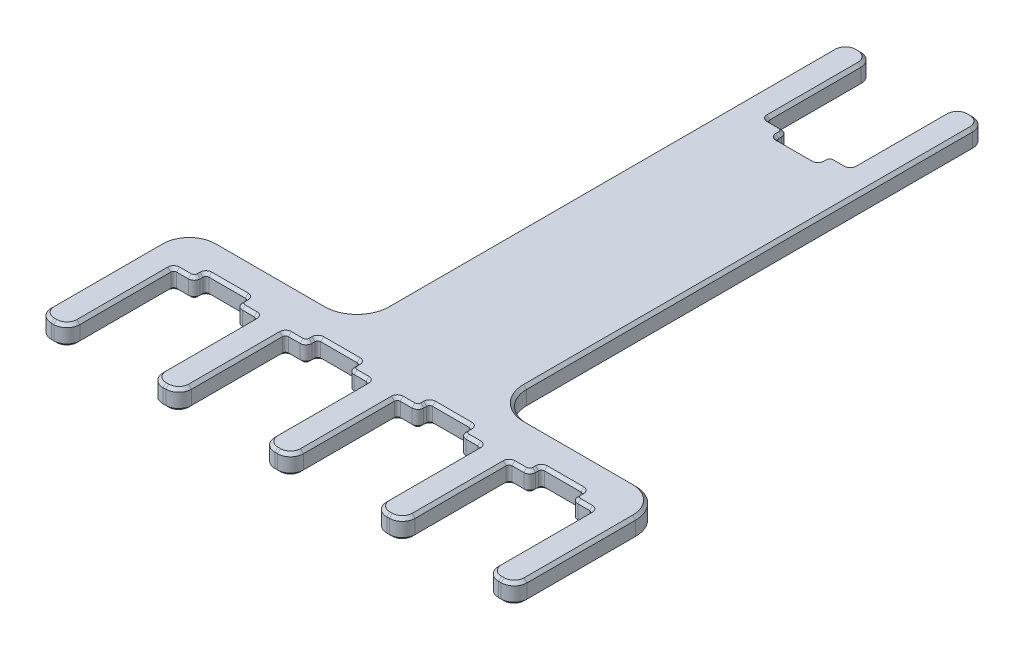
SolidWorks part; units mm, degrees
ref_plane "Front Plane" through (0, 0, 0) normal (0, 0, 1) x (1, 0, 0)
ref_plane "Top Plane" through (0, 0, 0) normal (0, 1, 0) x (1, 0, 0)
ref_plane "Right Plane" through (0, 0, 0) normal (1, 0, 0) x (0, 0, -1)
sketch "Sketch2" plane through (0, 0, 0) normal (0, 1, 0) x (1, 0, 0)
  line L0 (-5.2417, -1.575) -> (8.9583, -1.575)
  line L1 (-24.2917, -1.575) -> (-10.0917, -1.575)
  line L2 (-24.2917, -1.575) -> (-24.2917, -15.775)
  line L3 (-24.2917, -15.775) -> (-10.0917, -15.775)
  line L4 (-10.0917, -1.575) -> (-10.0917, -15.775)
  line L17 (-5.2417, -1.575) -> (-5.2417, -15.775)
  line L18 (-5.2417, -15.775) -> (8.9583, -15.775)
  line L19 (8.9583, -1.575) -> (8.9583, -15.775)
  line L20 (13.8083, -1.575) -> (28.0083, -1.575)
  line L21 (13.8083, -1.575) -> (13.8083, -15.775)
  line L22 (13.8083, -15.775) -> (28.0083, -15.775)
  line L23 (28.0083, -1.575) -> (28.0083, -15.775)
  line L24 (32.8583, -1.575) -> (47.0583, -1.575)
  line L25 (32.8583, -1.575) -> (32.8583, -15.775)
  line L26 (32.8583, -15.775) -> (47.0583, -15.775)
  line L27 (47.0583, -1.575) -> (47.0583, -15.775)
  line L28 (1.8583, -1.575) -> (1.8583, -15.775) construction
  line L29 (-17.1917, -15.775) -> (-17.1917, -1.575) construction
  dimension "D1" = 14.2
  dimension "D3" = 19.05
  dimension "D2" = 4
sketch "Sketch1" plane through (0, 0, 0) normal (0, 1, 0) x (1, 0, 0)
  line L0 (-29.1417, 5.925) -> (-0.5667, 5.925)
  line L1 (-0.5667, 5.925) -> (-0.5667, 89.125)
  line L3 (23.3333, 89.125) -> (23.3333, 5.925)
  line L4 (23.3333, 5.925) -> (51.9083, 5.925)
  line L5 (51.9083, 5.925) -> (51.9083, -19.775)
  line L6 (51.9083, -19.775) -> (-29.1417, -19.775)
  line L7 (-29.1417, -19.775) -> (-29.1417, 5.925)
  line L8 (-5.2417, -8.675) -> (-10.0917, -8.675) construction
  line L9 (-5.2417, -1.575) -> (-5.2417, -15.775) construction
  line L10 (-10.0917, -1.575) -> (-10.0917, -15.775) construction
  line L11 (47.0583, -8.675) -> (51.9083, -8.675) construction
  line L12 (47.0583, -1.575) -> (47.0583, -15.775) construction
  line L13 (-24.2917, -8.675) -> (-29.1417, -8.675) construction
  line L14 (-24.2917, -1.575) -> (-24.2917, -15.775) construction
  line L15 (18.4833, 70.925) -> (23.3333, 70.925) construction
  line L17 (-17.1917, -1.575) -> (-17.1917, -19.775) construction
  line L19 (-24.2917, -15.775) -> (-10.0917, -15.775) construction
  line L20 (-24.2917, -1.575) -> (-10.0917, -1.575) construction
  line L21 (4.2833, 89.125) -> (4.2833, 70.925)
  line L22 (4.2833, 70.925) -> (18.4833, 70.925)
  line L23 (18.4833, 70.925) -> (18.4833, 89.125)
  line L24 (-0.5667, 89.125) -> (4.2833, 89.125)
  line L25 (18.4833, 89.125) -> (23.3333, 89.125)
  line L26 (13.8083, -1.575) -> (28.0083, -1.575) construction
  line L27 (8.9583, -8.675) -> (13.8083, -8.675) construction
  line L28 (8.9583, -1.575) -> (8.9583, -15.775) construction
  line L29 (13.8083, -1.575) -> (13.8083, -15.775) construction
  line L30 (11.3833, 70.925) -> (11.3833, 89.125) construction
  line L31 (11.3833, -8.675) -> (11.3833, 70.925) construction
  line L32 (4.2833, 89.125) -> (18.4833, 89.125) construction
  point P27 (0, 0)
  dimension "D1" = 4
  dimension "D2" = 7.5
  dimension "D3" = 65
extrude "Boss-Extrude1" add sketch "Sketch1" along normal blind 3.4
sketch "Sketch3" plane through (0, 3.4, 0) normal (0, 1, 0) x (1, 0, 0)
  line L0 (-29.1417, -19.775) -> (51.9083, -19.775) construction
  line L2 (-24.2917, -1.575) -> (-24.2917, -19.775)
  line L3 (-24.2917, -19.775) -> (-10.0917, -19.775)
  line L4 (-10.0917, -1.575) -> (-10.0917, -19.775)
  line L5 (32.8583, -15.775) -> (47.0583, -15.775) construction
  line L7 (-5.2417, -1.575) -> (-5.2417, -19.775)
  line L8 (-5.2417, -19.775) -> (8.9583, -19.775)
  line L9 (8.9583, -1.575) -> (8.9583, -19.775)
  line L11 (13.8083, -1.575) -> (13.8083, -19.775)
  line L12 (13.8083, -19.775) -> (28.0083, -19.775)
  line L13 (28.0083, -1.575) -> (28.0083, -19.775)
  line L15 (32.8583, -1.575) -> (32.8583, -19.775)
  line L16 (32.8583, -19.775) -> (47.0583, -19.775)
  line L17 (47.0583, -1.575) -> (47.0583, -19.775)
  line L18 (-24.2917, -1.575) -> (-20.7917, -1.575)
  line L19 (-20.7917, -1.575) -> (-20.7917, 0.425)
  line L20 (-20.7917, 0.425) -> (-13.5917, 0.425)
  line L21 (-13.5917, 0.425) -> (-13.5917, -1.575)
  line L22 (-13.5917, -1.575) -> (-10.0917, -1.575)
  line L23 (-5.2417, -1.575) -> (-1.7417, -1.575)
  line L24 (-1.7417, -1.575) -> (-1.7417, 0.425)
  line L25 (-1.7417, 0.425) -> (5.4583, 0.425)
  line L26 (5.4583, 0.425) -> (5.4583, -1.575)
  line L27 (5.4583, -1.575) -> (8.9583, -1.575)
  line L28 (13.8083, -1.575) -> (17.3083, -1.575)
  line L29 (17.3083, -1.575) -> (17.3083, 0.425)
  line L30 (17.3083, 0.425) -> (24.5083, 0.425)
  line L31 (24.5083, 0.425) -> (24.5083, -1.575)
  line L32 (24.5083, -1.575) -> (28.0083, -1.575)
  line L33 (32.8583, -1.575) -> (36.3583, -1.575)
  line L34 (36.3583, -1.575) -> (36.3583, 0.425)
  line L35 (36.3583, 0.425) -> (43.5583, 0.425)
  line L36 (43.5583, 0.425) -> (43.5583, -1.575)
  line L37 (43.5583, -1.575) -> (47.0583, -1.575)
  line L38 (7.7833, 70.925) -> (7.7833, 68.925)
  line L39 (18.4833, 70.925) -> (4.2833, 70.925) construction
  line L40 (7.7833, 68.925) -> (14.9833, 68.925)
  line L41 (14.9833, 68.925) -> (14.9833, 70.925)
  line L42 (7.7833, 70.925) -> (14.9833, 70.925)
  line L43 (4.2833, 70.925) -> (7.7833, 70.925) construction
  line L44 (14.9833, 70.925) -> (18.4833, 70.925) construction
  dimension "D1" = 3.5
  dimension "D2" = 2
extrude "Cut-Extrude1" cut sketch "Sketch3" against normal blind 3.4
fillet "Fillet1" radius 5 4 edges at (-29.1417, 1.7, -5.925) (51.9083, 1.7, -5.925) (23.3333, 1.7, -5.925) (-0.5667, 1.7, -5.925)
fillet "Fillet2" radius 2.2 14 edges at (-0.5667, 1.7, -89.125) (4.2833, 1.7, -89.125) (18.4833, 1.7, -89.125) (23.3333, 1.7, -89.125) (51.9083, 1.7, 19.775) (47.0583, 1.7, 19.775) (32.8583, 1.7, 19.775) (28.0083, 1.7, 19.775) (13.8083, 1.7, 19.775) (8.9583, 1.7, 19.775) (-5.2417, 1.7, 19.775) (-10.0917, 1.7, 19.775) (-24.2917, 1.7, 19.775) (-29.1417, 1.7, 19.775)
fillet "Fillet3" radius 0.5 20 edges at (17.3083, 1.7, -0.425) (-1.7417, 1.7, -0.425) (-20.7917, 1.7, -0.425) (-13.5917, 1.7, -0.425) (5.4583, 1.7, -0.425) (24.5083, 1.7, -0.425) (36.3583, 1.7, -0.425) (43.5583, 1.7, -0.425) (47.0583, 1.7, 1.575) (32.8583, 1.7, 1.575) (13.8083, 1.7, 1.575) (28.0083, 1.7, 1.575) (8.9583, 1.7, 1.575) (-5.2417, 1.7, 1.575) (-10.0917, 1.7, 1.575) (-24.2917, 1.7, 1.575) (7.7833, 1.7, -68.925) (14.9833, 1.7, -68.925) (18.4833, 1.7, -70.925) (4.2833, 1.7, -70.925)
fillet "Fillet4" radius 1 10 edges at (-13.5917, 1.7, 1.575) (-1.7417, 1.7, 1.575) (5.4583, 1.7, 1.575) (17.3083, 1.7, 1.575) (24.5083, 1.7, 1.575) (36.3583, 1.7, 1.575) (43.5583, 1.7, 1.575) (-20.7917, 1.7, 1.575) (14.9833, 1.7, -70.925) (7.7833, 1.7, -70.925)
chamfer "Chamfer1" distance 0.5 192 edges at (-1.7417, 0, 0.325) (-1.5952, 0, -0.2786) (-2.0346, 0, 1.2821) (1.8583, 0, -0.425) (-3.7417, 0, 1.575) (5.3119, 0, -0.2786) (-5.0952, 0, 1.7214) (5.4583, 0, 0.325) (-5.2417, 0, 9.825) (5.7512, 0, 1.2821) (-5.886, 0, 19.1306) (7.4583, 0, 1.575) (-7.6667, 0, 19.775) (8.8119, 0, 1.7214) (-9.4473, 0, 19.1306) (8.9583, 0, 9.825) (-10.0917, 0, 9.825) (9.6027, 0, 19.1306) (-10.2381, 0, 1.7214) (11.3833, 0, 19.775) (-11.5917, 0, 1.575) (13.164, 0, 19.1306) (-13.2988, 0, 1.2821) (13.8083, 0, 9.825) (-13.5917, 0, 0.325) (13.9548, 0, 1.7214) (-13.7381, 0, -0.2786) (15.3083, 0, 1.575) (-17.1917, 0, -0.425) (17.0154, 0, 1.2821) (-20.6452, 0, -0.2786) (17.3083, 0, 0.325) (-20.7917, 0, 0.325) (17.4548, 0, -0.2786) (-21.0846, 0, 1.2821) (20.9083, 0, -0.425) (-22.7917, 0, 1.575) (24.3619, 0, -0.2786) (-24.1452, 0, 1.7214) (24.5083, 0, 0.325) (-24.2917, 0, 9.825) (24.8012, 0, 1.2821) (-24.936, 0, 19.1306) (26.5083, 0, 1.575) (-26.7167, 0, 19.775) (27.8619, 0, 1.7214) (-28.4973, 0, 19.1306) (28.0083, 0, 9.825) (-29.1417, 0, 8.325) (28.6527, 0, 19.1306) (-27.6772, 0, -4.4605) (30.4333, 0, 19.775) (-14.8542, 0, -5.925) (32.214, 0, 19.1306) (-2.0311, 0, -7.3895) (32.8583, 0, 9.825) (-0.5667, 0, -48.925) (33.0048, 0, 1.7214) (0.0777, 0, -88.4806) (34.3583, 0, 1.575) (1.8583, 0, -89.125) (36.0654, 0, 1.2821) (3.639, 0, -88.4806) (36.3583, 0, 0.325) (4.2833, 0, -79.175) (36.5048, 0, -0.2786) (4.4298, 0, -71.0714) (39.9583, 0, -0.425) (5.7833, 0, -70.925) (43.4119, 0, -0.2786) (7.4904, 0, -70.6321) (43.5583, 0, 0.325) (7.7833, 0, -69.675) (43.8512, 0, 1.2821) (7.9298, 0, -69.0714) (45.5583, 0, 1.575) (11.3833, 0, -68.925) (46.9119, 0, 1.7214) (14.8369, 0, -69.0714) (47.0583, 0, 9.825) (14.9833, 0, -69.675) (47.7027, 0, 19.1306) (15.2762, 0, -70.6321) (49.4833, 0, 19.775) (16.9833, 0, -70.925) (51.264, 0, 19.1306) (18.3369, 0, -71.0714) (51.9083, 0, 8.325) (18.4833, 0, -79.175) (50.4439, 0, -4.4605) (19.1277, 0, -88.4806) (37.6208, 0, -5.925) (20.9083, 0, -89.125) (24.7978, 0, -7.3895) (22.689, 0, -88.4806) (23.3333, 0, -48.925) (-1.7417, 3.4, 0.325) (-1.5952, 3.4, -0.2786) (-2.0346, 3.4, 1.2821) (1.8583, 3.4, -0.425) (-3.7417, 3.4, 1.575) (5.3119, 3.4, -0.2786) (-5.0952, 3.4, 1.7214) (5.4583, 3.4, 0.325) (-5.2417, 3.4, 9.825) (5.7512, 3.4, 1.2821) (-5.886, 3.4, 19.1306) (7.4583, 3.4, 1.575) (-7.6667, 3.4, 19.775) (8.8119, 3.4, 1.7214) (-9.4473, 3.4, 19.1306) (8.9583, 3.4, 9.825) (-10.0917, 3.4, 9.825) (9.6027, 3.4, 19.1306) (-10.2381, 3.4, 1.7214) (11.3833, 3.4, 19.775) (-11.5917, 3.4, 1.575) (13.164, 3.4, 19.1306) (-13.2988, 3.4, 1.2821) (13.8083, 3.4, 9.825) (-13.5917, 3.4, 0.325) (13.9548, 3.4, 1.7214) (-13.7381, 3.4, -0.2786) (15.3083, 3.4, 1.575) (-17.1917, 3.4, -0.425) (17.0154, 3.4, 1.2821) (-20.6452, 3.4, -0.2786) (17.3083, 3.4, 0.325) (-20.7917, 3.4, 0.325) (17.4548, 3.4, -0.2786) (-21.0846, 3.4, 1.2821) (20.9083, 3.4, -0.425) (-22.7917, 3.4, 1.575) (24.3619, 3.4, -0.2786) (-24.1452, 3.4, 1.7214) (24.5083, 3.4, 0.325) (-24.2917, 3.4, 9.825) (24.8012, 3.4, 1.2821) (-24.936, 3.4, 19.1306) (26.5083, 3.4, 1.575) (-26.7167, 3.4, 19.775) (27.8619, 3.4, 1.7214) (-28.4973, 3.4, 19.1306) (28.0083, 3.4, 9.825) (-29.1417, 3.4, 8.325) (28.6527, 3.4, 19.1306) (-27.6772, 3.4, -4.4605) (30.4333, 3.4, 19.775) (-14.8542, 3.4, -5.925) (32.214, 3.4, 19.1306) (-2.0311, 3.4, -7.3895) (32.8583, 3.4, 9.825) (-0.5667, 3.4, -48.925) (33.0048, 3.4, 1.7214) (0.0777, 3.4, -88.4806) (34.3583, 3.4, 1.575) (1.8583, 3.4, -89.125) (36.0654, 3.4, 1.2821) (3.639, 3.4, -88.4806) (36.3583, 3.4, 0.325) (4.2833, 3.4, -79.175) (36.5048, 3.4, -0.2786) (4.4298, 3.4, -71.0714) (39.9583, 3.4, -0.425) (5.7833, 3.4, -70.925) (43.4119, 3.4, -0.2786) (7.4904, 3.4, -70.6321) (43.5583, 3.4, 0.325) (7.7833, 3.4, -69.675) (43.8512, 3.4, 1.2821) (7.9298, 3.4, -69.0714) (45.5583, 3.4, 1.575) (11.3833, 3.4, -68.925) (46.9119, 3.4, 1.7214) (14.8369, 3.4, -69.0714) (47.0583, 3.4, 9.825) (14.9833, 3.4, -69.675) (47.7027, 3.4, 19.1306) (15.2762, 3.4, -70.6321) (49.4833, 3.4, 19.775) (16.9833, 3.4, -70.925) (51.264, 3.4, 19.1306) (18.3369, 3.4, -71.0714) (51.9083, 3.4, 8.325) (18.4833, 3.4, -79.175) (50.4439, 3.4, -4.4605) (19.1277, 3.4, -88.4806) (37.6208, 3.4, -5.925) (20.9083, 3.4, -89.125) (24.7978, 3.4, -7.3895) (22.689, 3.4, -88.4806) (23.3333, 3.4, -48.925)
